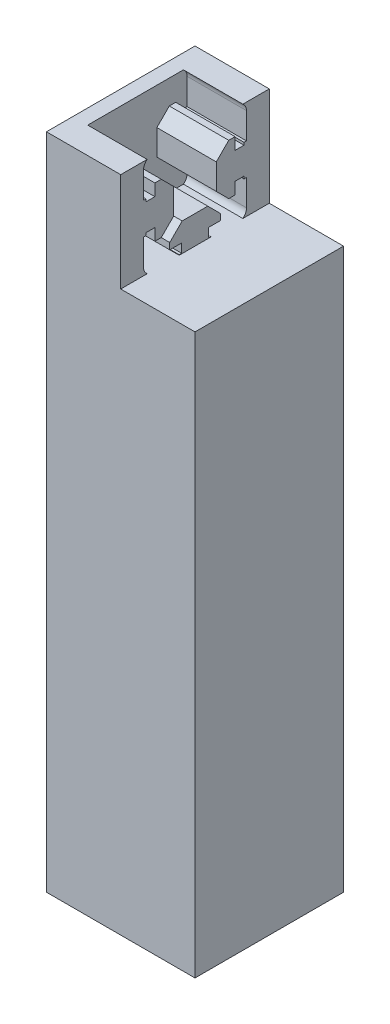
SolidWorks part; units mm, degrees
ref_plane "前视基准面" through (0, 0, 0) normal (0, 0, 1) x (1, 0, 0)
ref_plane "上视基准面" through (0, 0, 0) normal (0, 1, 0) x (1, 0, 0)
ref_plane "右视基准面" through (0, 0, 0) normal (1, 0, 0) x (0, 0, -1)
other "Configuration Table"
sketch "草图2" plane through (0, 0, 0) normal (0, 1, 0) x (1, 0, 0)
  line L1 (0, 0) -> (30, 0)
  line L2 (0, 0) -> (0, 30)
  line L3 (0, 30) -> (30, 30)
  line L4 (30, 0) -> (30, 30)
  dimension "D1" = 30
  dimension "D2" = 30
extrude "凸台-拉伸1" add sketch "草图2" along normal blind 113
sketch "草图3" plane through (0, 0, 0) normal (-1, 0, 0) x (0, 0, 1)
  line L0 (-120, 133) -> (90, 133) construction
  line L1 (-30, 113) -> (0, 113)
  line L2 (-30, 113) -> (-30, 133)
  line L3 (-30, 133) -> (0, 133)
  line L4 (0, 113) -> (0, 133)
  line L6 (-30, 113) -> (-30, 0) construction
  line L7 (0, 113) -> (0, 0) construction
  line L60 (-6.5, 133) -> (-11.4, 133)
  line L61 (-11.4, 133) -> (-11.4, 132.5)
  line L62 (-11.4, 132.5) -> (-11.9, 132.5)
  line L63 (-11.9, 132.5) -> (-11.9, 131.5)
  line L64 (-11.9, 131.5) -> (-9.5, 131.5)
  line L65 (-9.5, 131.5) -> (-9.5, 129.65)
  line L66 (-9.5, 129.65) -> (-12.25, 126.9)
  line L67 (-12.25, 126.9) -> (-17.75, 126.9)
  line L68 (-17.75, 126.9) -> (-20.5, 129.65)
  line L69 (-20.5, 129.65) -> (-20.5, 131.5)
  line L70 (-20.5, 131.5) -> (-18.1, 131.5)
  line L71 (-18.1, 131.5) -> (-18.1, 132.5)
  line L72 (-18.1, 132.5) -> (-18.6, 132.5)
  line L73 (-18.6, 132.5) -> (-18.6, 133)
  line L74 (-18.6, 133) -> (-23.5, 133)
  line L75 (-25, 131.5) -> (-25, 126.6)
  line L76 (-25, 126.6) -> (-24.5, 126.6)
  line L77 (-24.5, 126.6) -> (-24.5, 126.1)
  line L78 (-24.5, 126.1) -> (-23.5, 126.1)
  line L79 (-23.5, 126.1) -> (-23.5, 128.5)
  line L80 (-23.5, 128.5) -> (-21.65, 128.5)
  line L81 (-21.65, 128.5) -> (-18.9, 125.75)
  line L82 (-18.9, 125.75) -> (-18.9, 120.25)
  line L83 (-18.9, 120.25) -> (-21.65, 117.5)
  line L84 (-21.65, 117.5) -> (-23.5, 117.5)
  line L85 (-23.5, 117.5) -> (-23.5, 119.9)
  line L86 (-23.5, 119.9) -> (-24.5, 119.9)
  line L87 (-24.5, 119.9) -> (-24.5, 119.4)
  line L88 (-24.5, 119.4) -> (-25, 119.4)
  line L89 (-25, 119.4) -> (-25, 114.5)
  line L90 (-23.5, 113) -> (-18.6, 113)
  line L91 (-18.6, 113) -> (-18.6, 113.5)
  line L92 (-18.6, 113.5) -> (-18.1, 113.5)
  line L93 (-18.1, 113.5) -> (-18.1, 114.5)
  line L94 (-18.1, 114.5) -> (-20.5, 114.5)
  line L95 (-20.5, 114.5) -> (-20.5, 116.35)
  line L96 (-20.5, 116.35) -> (-17.75, 119.1)
  line L97 (-17.75, 119.1) -> (-12.25, 119.1)
  line L98 (-12.25, 119.1) -> (-9.5, 116.35)
  line L99 (-9.5, 116.35) -> (-9.5, 114.5)
  line L100 (-9.5, 114.5) -> (-11.9, 114.5)
  line L101 (-11.9, 114.5) -> (-11.9, 113.5)
  line L102 (-11.9, 113.5) -> (-11.4, 113.5)
  line L103 (-11.4, 113.5) -> (-11.4, 113)
  line L104 (-11.4, 113) -> (-6.5, 113)
  line L105 (-5, 114.5) -> (-5, 119.4)
  line L106 (-5, 119.4) -> (-5.5, 119.4)
  line L107 (-5.5, 119.4) -> (-5.5, 119.9)
  line L108 (-5.5, 119.9) -> (-6.5, 119.9)
  line L109 (-6.5, 119.9) -> (-6.5, 117.5)
  line L110 (-6.5, 117.5) -> (-8.35, 117.5)
  line L111 (-8.35, 117.5) -> (-11.1, 120.25)
  line L112 (-11.1, 120.25) -> (-11.1, 125.75)
  line L113 (-11.1, 125.75) -> (-8.35, 128.5)
  line L114 (-8.35, 128.5) -> (-6.5, 128.5)
  line L115 (-6.5, 128.5) -> (-6.5, 126.1)
  line L116 (-6.5, 126.1) -> (-5.5, 126.1)
  line L117 (-5.5, 126.1) -> (-5.5, 126.6)
  line L118 (-5.5, 126.6) -> (-5, 126.6)
  line L119 (-5, 126.6) -> (-5, 131.5)
  line L120 (-6.5, 133) -> (-11.4, 133)
  line L121 (-11.4, 133) -> (-11.4, 132.5)
  line L122 (-11.4, 132.5) -> (-11.9, 132.5)
  line L123 (-11.9, 132.5) -> (-11.9, 131.5)
  line L124 (-11.9, 131.5) -> (-9.5, 131.5)
  line L125 (-9.5, 131.5) -> (-9.5, 129.65)
  line L126 (-9.5, 129.65) -> (-12.25, 126.9)
  line L127 (-12.25, 126.9) -> (-17.75, 126.9)
  line L128 (-17.75, 126.9) -> (-20.5, 129.65)
  line L129 (-20.5, 129.65) -> (-20.5, 131.5)
  line L130 (-20.5, 131.5) -> (-18.1, 131.5)
  line L131 (-18.1, 131.5) -> (-18.1, 132.5)
  line L132 (-18.1, 132.5) -> (-18.6, 132.5)
  line L133 (-18.6, 132.5) -> (-18.6, 133)
  line L134 (-18.6, 133) -> (-23.5, 133)
  line L135 (-25, 131.5) -> (-25, 126.6)
  line L136 (-25, 126.6) -> (-24.5, 126.6)
  line L137 (-24.5, 126.6) -> (-24.5, 126.1)
  line L138 (-24.5, 126.1) -> (-23.5, 126.1)
  line L139 (-23.5, 126.1) -> (-23.5, 128.5)
  line L140 (-23.5, 128.5) -> (-21.65, 128.5)
  line L141 (-21.65, 128.5) -> (-18.9, 125.75)
  line L142 (-18.9, 125.75) -> (-18.9, 120.25)
  line L143 (-18.9, 120.25) -> (-21.65, 117.5)
  line L144 (-21.65, 117.5) -> (-23.5, 117.5)
  line L145 (-23.5, 117.5) -> (-23.5, 119.9)
  line L146 (-23.5, 119.9) -> (-24.5, 119.9)
  line L147 (-24.5, 119.9) -> (-24.5, 119.4)
  line L148 (-24.5, 119.4) -> (-25, 119.4)
  line L149 (-25, 119.4) -> (-25, 114.5)
  line L150 (-23.5, 113) -> (-18.6, 113)
  line L151 (-18.6, 113) -> (-18.6, 113.5)
  line L152 (-18.6, 113.5) -> (-18.1, 113.5)
  line L153 (-18.1, 113.5) -> (-18.1, 114.5)
  line L154 (-18.1, 114.5) -> (-20.5, 114.5)
  line L155 (-20.5, 114.5) -> (-20.5, 116.35)
  line L156 (-20.5, 116.35) -> (-17.75, 119.1)
  line L157 (-17.75, 119.1) -> (-12.25, 119.1)
  line L158 (-12.25, 119.1) -> (-9.5, 116.35)
  line L159 (-9.5, 116.35) -> (-9.5, 114.5)
  line L160 (-9.5, 114.5) -> (-11.9, 114.5)
  line L161 (-11.9, 114.5) -> (-11.9, 113.5)
  line L162 (-11.9, 113.5) -> (-11.4, 113.5)
  line L163 (-11.4, 113.5) -> (-11.4, 113)
  line L164 (-11.4, 113) -> (-6.5, 113)
  line L165 (-5, 114.5) -> (-5, 119.4)
  line L166 (-5, 119.4) -> (-5.5, 119.4)
  line L167 (-5.5, 119.4) -> (-5.5, 119.9)
  line L168 (-5.5, 119.9) -> (-6.5, 119.9)
  line L169 (-6.5, 119.9) -> (-6.5, 117.5)
  line L170 (-6.5, 117.5) -> (-8.35, 117.5)
  line L171 (-8.35, 117.5) -> (-11.1, 120.25)
  line L172 (-11.1, 120.25) -> (-11.1, 125.75)
  line L173 (-11.1, 125.75) -> (-8.35, 128.5)
  line L174 (-8.35, 128.5) -> (-6.5, 128.5)
  line L175 (-6.5, 128.5) -> (-6.5, 126.1)
  line L176 (-6.5, 126.1) -> (-5.5, 126.1)
  line L177 (-5.5, 126.1) -> (-5.5, 126.6)
  line L178 (-5.5, 126.6) -> (-5, 126.6)
  line L179 (-5, 126.6) -> (-5, 131.5)
  line L244 (-6.5, 133.4) -> (-11.8, 133.4)
  line L245 (-11.8, 133.4) -> (-11.8, 132.9)
  line L246 (-11.8, 132.9) -> (-12.3, 132.9)
  line L247 (-12.3, 132.9) -> (-12.3, 131.1)
  line L248 (-12.3, 131.1) -> (-9.9, 131.1)
  line L249 (-9.9, 131.1) -> (-9.9, 129.8157)
  line L250 (-9.9, 129.8157) -> (-12.4157, 127.3)
  line L251 (-12.4157, 127.3) -> (-17.5843, 127.3)
  line L252 (-17.5843, 127.3) -> (-20.1, 129.8157)
  line L253 (-20.1, 129.8157) -> (-20.1, 131.1)
  line L254 (-20.1, 131.1) -> (-17.7, 131.1)
  line L255 (-17.7, 131.1) -> (-17.7, 132.9)
  line L256 (-17.7, 132.9) -> (-18.2, 132.9)
  line L257 (-18.2, 132.9) -> (-18.2, 133.4)
  line L258 (-18.2, 133.4) -> (-23.5, 133.4)
  line L259 (-25.4, 131.5) -> (-25.4, 126.2)
  line L260 (-25.4, 126.2) -> (-24.9, 126.2)
  line L261 (-24.9, 126.2) -> (-24.9, 125.7)
  line L262 (-24.9, 125.7) -> (-23.1, 125.7)
  line L263 (-23.1, 125.7) -> (-23.1, 128.1)
  line L264 (-23.1, 128.1) -> (-21.8157, 128.1)
  line L265 (-21.8157, 128.1) -> (-19.3, 125.5843)
  line L266 (-19.3, 125.5843) -> (-19.3, 120.4157)
  line L267 (-19.3, 120.4157) -> (-21.8157, 117.9)
  line L268 (-21.8157, 117.9) -> (-23.1, 117.9)
  line L269 (-23.1, 117.9) -> (-23.1, 120.3)
  line L270 (-23.1, 120.3) -> (-24.9, 120.3)
  line L271 (-24.9, 120.3) -> (-24.9, 119.8)
  line L272 (-24.9, 119.8) -> (-25.4, 119.8)
  line L273 (-25.4, 119.8) -> (-25.4, 114.5)
  line L274 (-23.5, 112.6) -> (-18.2, 112.6)
  line L275 (-18.2, 112.6) -> (-18.2, 113.1)
  line L276 (-18.2, 113.1) -> (-17.7, 113.1)
  line L277 (-17.7, 113.1) -> (-17.7, 114.9)
  line L278 (-17.7, 114.9) -> (-20.1, 114.9)
  line L279 (-20.1, 114.9) -> (-20.1, 116.1843)
  line L280 (-20.1, 116.1843) -> (-17.5843, 118.7)
  line L281 (-17.5843, 118.7) -> (-12.4157, 118.7)
  line L282 (-12.4157, 118.7) -> (-9.9, 116.1843)
  line L283 (-9.9, 116.1843) -> (-9.9, 114.9)
  line L284 (-9.9, 114.9) -> (-12.3, 114.9)
  line L285 (-12.3, 114.9) -> (-12.3, 113.1)
  line L286 (-12.3, 113.1) -> (-11.8, 113.1)
  line L287 (-11.8, 113.1) -> (-11.8, 112.6)
  line L288 (-11.8, 112.6) -> (-6.5, 112.6)
  line L289 (-4.6, 114.5) -> (-4.6, 119.8)
  line L290 (-4.6, 119.8) -> (-5.1, 119.8)
  line L291 (-5.1, 119.8) -> (-5.1, 120.3)
  line L292 (-5.1, 120.3) -> (-6.9, 120.3)
  line L293 (-6.9, 120.3) -> (-6.9, 117.9)
  line L294 (-6.9, 117.9) -> (-8.1843, 117.9)
  line L295 (-8.1843, 117.9) -> (-10.7, 120.4157)
  line L296 (-10.7, 120.4157) -> (-10.7, 125.5843)
  line L297 (-10.7, 125.5843) -> (-8.1843, 128.1)
  line L298 (-8.1843, 128.1) -> (-6.9, 128.1)
  line L299 (-6.9, 128.1) -> (-6.9, 125.7)
  line L300 (-6.9, 125.7) -> (-5.1, 125.7)
  line L301 (-5.1, 125.7) -> (-5.1, 126.2)
  line L302 (-5.1, 126.2) -> (-4.6, 126.2)
  line L303 (-4.6, 126.2) -> (-4.6, 131.5)
  line L304 (-6.5, 133.4) -> (-11.8, 133.4)
  line L305 (-11.8, 133.4) -> (-11.8, 132.9)
  line L306 (-11.8, 132.9) -> (-12.3, 132.9)
  line L307 (-12.3, 132.9) -> (-12.3, 131.1)
  line L308 (-12.3, 131.1) -> (-9.9, 131.1)
  line L309 (-9.9, 131.1) -> (-9.9, 129.8157)
  line L310 (-9.9, 129.8157) -> (-12.4157, 127.3)
  line L311 (-12.4157, 127.3) -> (-17.5843, 127.3)
  line L312 (-17.5843, 127.3) -> (-20.1, 129.8157)
  line L313 (-20.1, 129.8157) -> (-20.1, 131.1)
  line L314 (-20.1, 131.1) -> (-17.7, 131.1)
  line L315 (-17.7, 131.1) -> (-17.7, 132.9)
  line L316 (-17.7, 132.9) -> (-18.2, 132.9)
  line L317 (-18.2, 132.9) -> (-18.2, 133.4)
  line L318 (-18.2, 133.4) -> (-23.5, 133.4)
  line L319 (-25.4, 131.5) -> (-25.4, 126.2)
  line L320 (-25.4, 126.2) -> (-24.9, 126.2)
  line L321 (-24.9, 126.2) -> (-24.9, 125.7)
  line L322 (-24.9, 125.7) -> (-23.1, 125.7)
  line L323 (-23.1, 125.7) -> (-23.1, 128.1)
  line L324 (-23.1, 128.1) -> (-21.8157, 128.1)
  line L325 (-21.8157, 128.1) -> (-19.3, 125.5843)
  line L326 (-19.3, 125.5843) -> (-19.3, 120.4157)
  line L327 (-19.3, 120.4157) -> (-21.8157, 117.9)
  line L328 (-21.8157, 117.9) -> (-23.1, 117.9)
  line L329 (-23.1, 117.9) -> (-23.1, 120.3)
  line L330 (-23.1, 120.3) -> (-24.9, 120.3)
  line L331 (-24.9, 120.3) -> (-24.9, 119.8)
  line L332 (-24.9, 119.8) -> (-25.4, 119.8)
  line L333 (-25.4, 119.8) -> (-25.4, 114.5)
  line L334 (-23.5, 112.6) -> (-18.2, 112.6)
  line L335 (-18.2, 112.6) -> (-18.2, 113.1)
  line L336 (-18.2, 113.1) -> (-17.7, 113.1)
  line L337 (-17.7, 113.1) -> (-17.7, 114.9)
  line L338 (-17.7, 114.9) -> (-20.1, 114.9)
  line L339 (-20.1, 114.9) -> (-20.1, 116.1843)
  line L340 (-20.1, 116.1843) -> (-17.5843, 118.7)
  line L341 (-17.5843, 118.7) -> (-12.4157, 118.7)
  line L342 (-12.4157, 118.7) -> (-9.9, 116.1843)
  line L343 (-9.9, 116.1843) -> (-9.9, 114.9)
  line L344 (-9.9, 114.9) -> (-12.3, 114.9)
  line L345 (-12.3, 114.9) -> (-12.3, 113.1)
  line L346 (-12.3, 113.1) -> (-11.8, 113.1)
  line L347 (-11.8, 113.1) -> (-11.8, 112.6)
  line L348 (-11.8, 112.6) -> (-6.5, 112.6)
  line L349 (-4.6, 114.5) -> (-4.6, 119.8)
  line L350 (-4.6, 119.8) -> (-5.1, 119.8)
  line L351 (-5.1, 119.8) -> (-5.1, 120.3)
  line L352 (-5.1, 120.3) -> (-6.9, 120.3)
  line L353 (-6.9, 120.3) -> (-6.9, 117.9)
  line L354 (-6.9, 117.9) -> (-8.1843, 117.9)
  line L355 (-8.1843, 117.9) -> (-10.7, 120.4157)
  line L356 (-10.7, 120.4157) -> (-10.7, 125.5843)
  line L357 (-10.7, 125.5843) -> (-8.1843, 128.1)
  line L358 (-8.1843, 128.1) -> (-6.9, 128.1)
  line L359 (-6.9, 128.1) -> (-6.9, 125.7)
  line L360 (-6.9, 125.7) -> (-5.1, 125.7)
  line L361 (-5.1, 125.7) -> (-5.1, 126.2)
  line L362 (-5.1, 126.2) -> (-4.6, 126.2)
  line L363 (-4.6, 126.2) -> (-4.6, 131.5)
  arc A4 (-23.5, 133) -> (-25, 131.5) centre (-23.5, 131.5) ccw
  arc A5 (-25, 114.5) -> (-23.5, 113) centre (-23.5, 114.5) ccw
  arc A6 (-6.5, 113) -> (-5, 114.5) centre (-6.5, 114.5) ccw
  arc A7 (-5, 131.5) -> (-6.5, 133) centre (-6.5, 131.5) ccw
  arc A8 (-23.5, 133) -> (-25, 131.5) centre (-23.5, 131.5) ccw
  arc A9 (-25, 114.5) -> (-23.5, 113) centre (-23.5, 114.5) ccw
  arc A10 (-6.5, 113) -> (-5, 114.5) centre (-6.5, 114.5) ccw
  arc A11 (-5, 131.5) -> (-6.5, 133) centre (-6.5, 131.5) ccw
  arc A16 (-23.5, 133.4) -> (-25.4, 131.5) centre (-23.5, 131.5) ccw
  arc A17 (-25.4, 114.5) -> (-23.5, 112.6) centre (-23.5, 114.5) ccw
  arc A18 (-6.5, 112.6) -> (-4.6, 114.5) centre (-6.5, 114.5) ccw
  arc A19 (-4.6, 131.5) -> (-6.5, 133.4) centre (-6.5, 131.5) ccw
  arc A20 (-23.5, 133.4) -> (-25.4, 131.5) centre (-23.5, 131.5) ccw
  arc A21 (-25.4, 114.5) -> (-23.5, 112.6) centre (-23.5, 114.5) ccw
  arc A22 (-6.5, 112.6) -> (-4.6, 114.5) centre (-6.5, 114.5) ccw
  arc A23 (-4.6, 131.5) -> (-6.5, 133.4) centre (-6.5, 131.5) ccw
  point P18 (0, 0)
  point P20 (0, 120)
  point P22 (0, 140)
  point P28 (-30, 120)
  line M68 (0, 113) -> (-30, 113)
  dimension "D2" = 0.4
  dimension "D1" = 0
extrude "凸台-拉伸2" add sketch "草图3" against normal blind 15 contours A21 L333 L332 L331 L330 L329 L328 L327 L326 L325 L324 L323 L322 L321 L320 L319 L3 L2 L1 | A22 L4 L3 L363 L362 L361 L360 L359 L358 L357 L356 L355 L354 L353 L352 L351 L350 L349 M68 | L347 L346 L345 L344 L343 L342 L341 L340 L339 L338 L337 L336 L335 M68
sketch "草图4" plane through (0, 0, 0) normal (-1, 0, 0) x (0, 0, 1)
  line L0 (-120, 133) -> (90, 133) construction
  line L1 (-30, 113) -> (0, 113)
  line L2 (-30, 113) -> (-30, 133)
  line L3 (-30, 133) -> (0, 133)
  line L4 (0, 113) -> (0, 133)
  line L5 (0, 133) -> (0, 0) construction
  line L6 (-30, 133) -> (-30, 0) construction
  line L8 (0, 133) -> (0, 0) construction
  line L9 (-11.8, 113) -> (-5.3338, 113) construction
  point P7 (0, 120)
  point P10 (-30, 120.209)
  point P13 (0, 0)
  point P14 (-30, 119.4666)
  point P15 (-30, 120.0551)
  point P16 (0, 124.5263)
  point P17 (0, 129.552)
extrude "凸台-拉伸4" add sketch "草图4" against normal blind 3
